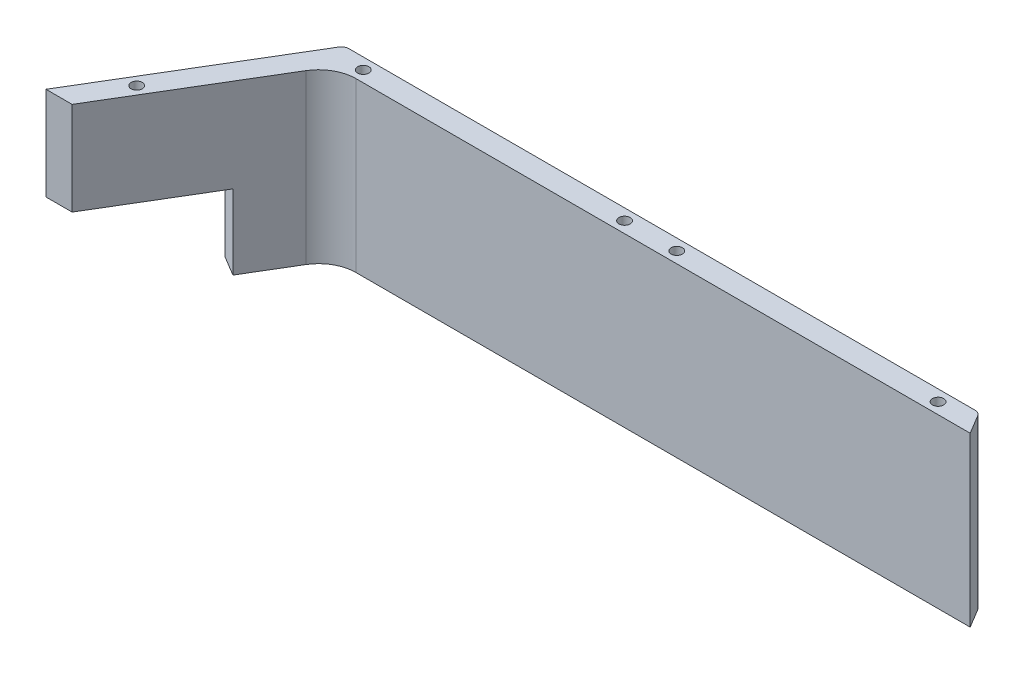
SolidWorks part; units mm, degrees
ref_plane "Front Plane" through (0, 0, 0) normal (0, 0, 1) x (1, 0, 0)
ref_plane "Top Plane" through (0, 0, 0) normal (0, 1, 0) x (1, 0, 0)
ref_plane "Right Plane" through (0, 0, 0) normal (1, 0, 0) x (0, 0, -1)
sketch "Sketch1" plane through (0, 0, 0) normal (0, 1, 0) x (1, 0, 0)
  line L0 (-115, 0) -> (-85, 50)
  line L1 (-85, 50) -> (85, 50)
  line L3 (81.6, 44) -> (-81.6, 44)
  line L4 (-81.6, 44) -> (-108, 0)
  line L5 (-108, 0) -> (-115, 0)
  line L6 (0, -55) -> (0, 55) construction
  line L7 (108, 0) -> (115, 0)
  line L8 (81.6, 44) -> (108, 0)
  line L9 (115, 0) -> (85, 50)
  dimension "D1" = 6
  dimension "D2" = 7
  dimension "D3" = 50
  dimension "D4" = 30
  dimension "D5" = 170
extrude "Boss-Extrude1" add sketch "Sketch1" along normal mid plane 45
sketch "Sketch2" plane through (0, 22.5, 0) normal (0, 1, 0) x (1, 0, 0)
  line L1 (-85, 50) -> (-115, 0) construction
  line L2 (85, 50) -> (-85, 50) construction
  line L3 (0, -55) -> (0, 55) construction
  circle A0 centre (-103.7014, 13) radius 1.5
  circle A1 centre (-77, 47) radius 1.5
  circle A2 centre (-7, 47) radius 1.5
  circle A3 centre (7, 47) radius 1.5
  circle A4 centre (77, 47) radius 1.5
  circle A5 centre (103.7014, 13) radius 1.5
  dimension "D2" = 3
  dimension "D3" = 3
  dimension "D5" = 3
  dimension "D1" = 70
  dimension "D4" = 7
  dimension "D6" = 3
  dimension "D7" = 3
  dimension "D8" = 3
  dimension "D9" = 37
extrude "Cut-Extrude1" cut sketch "Sketch2" against normal blind 5
fillet "Fillet1" radius 2 2 edges at (85, 0, -50) (-85, 0, -50)
sketch "Sketch3" plane through (-84.5588, 0, -50.7353) normal (-0.8575, 0, -0.5145) x (-0.5145, 0, 0.8575)
  line L0 (59.167, -22.5) -> (59.167, -2.5)
  line L1 (59.167, -22.5) -> (24.167, -22.5)
  line L3 (59.167, -2.5) -> (24.167, -2.5)
  line L4 (24.167, -22.5) -> (24.167, -2.5)
  line L5 (1.9899, 22.5) -> (59.167, 22.5) construction
  line L6 (59.167, 22.5) -> (59.167, -22.5) construction
  dimension "D1" = 25
  dimension "D2" = 35
  dimension "D3" = 20
  dimension "D4" = 0
extrude "Cut-Extrude2" cut sketch "Sketch3" against normal blind 10
sketch "Sketch6" plane through (0, 0, 0) normal (1, 0, 0) x (0, 0, -1)
  line L0 (0, -22.5) -> (49.029, -22.5) construction
  line L1 (0, 22.5) -> (44, 22.5)
  line L2 (0, 22.5) -> (0, -22.5)
  line L3 (0, -22.5) -> (44, -22.5)
  line L4 (44, 22.5) -> (44, -22.5)
  line L5 (50, 22.5) -> (50, -22.5) construction
  dimension "D1" = 6
extrude "Cut-Extrude3" cut sketch "Sketch6" along normal through all
fillet "Fillet2" radius 10 1 edges at (-81.6, 0, -44)
